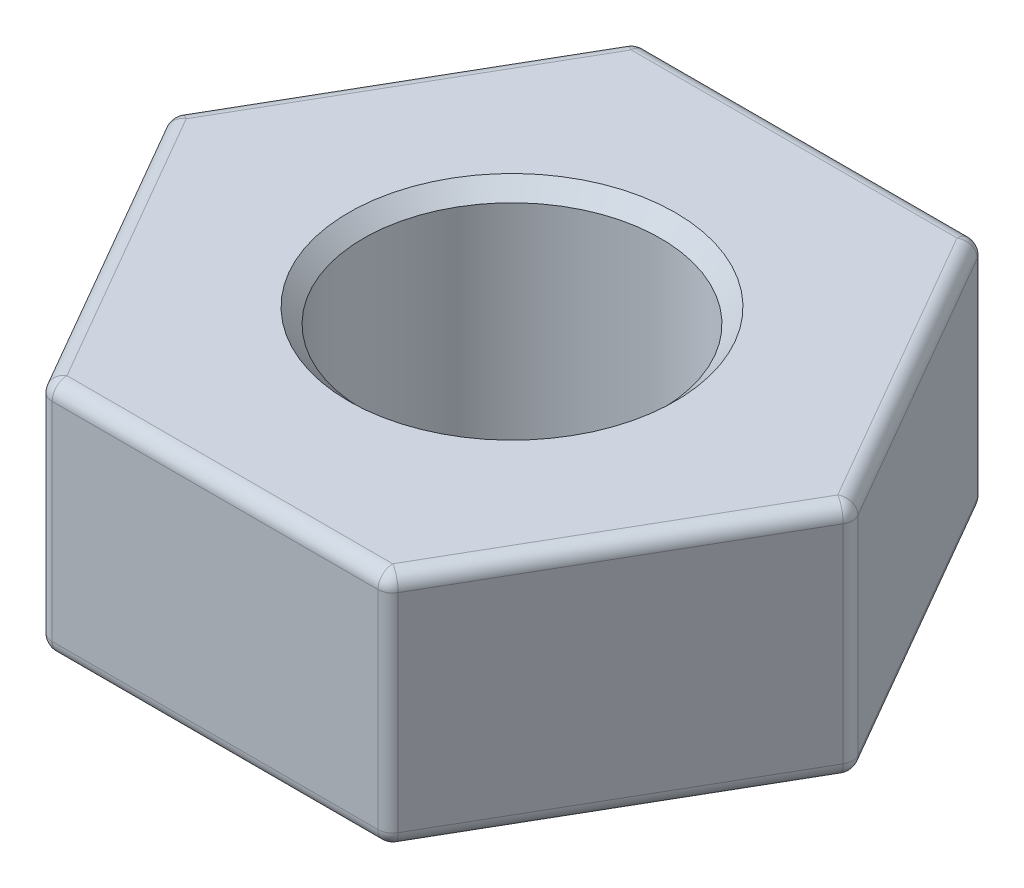
SolidWorks part; units mm, degrees
material "AISI 304"
ref_plane "前视基准面" through (0, 0, 0) normal (0, 0, 1) x (1, 0, 0)
ref_plane "上视基准面" through (0, 0, 0) normal (0, 1, 0) x (1, 0, 0)
ref_plane "右视基准面" through (0, 0, 0) normal (1, 0, 0) x (0, 0, -1)
sketch "草图2" plane through (0, 0, 0) normal (0, 1, 0) x (1, 0, 0)
  line L1 (2.3094, 0) -> (1.1547, 2)
  line L2 (1.1547, 2) -> (-1.1547, 2)
  line L3 (-1.1547, 2) -> (-2.3094, 0)
  line L4 (-2.3094, 0) -> (-1.1547, -2)
  line L5 (-1.1547, -2) -> (1.1547, -2)
  line L6 (1.1547, -2) -> (2.3094, 0)
  circle A0 centre (0, 0) radius 2 construction
  circle A1 centre (0, 0) radius 1
  dimension "D2" = 2
  dimension "D1" = 4
extrude "凸台-拉伸1" add sketch "草图2" along normal blind 1.6
fillet "圆角1" radius 0.1 18 edges at (-1.7321, 0, 1) (-1.7321, 0, -1) (0, 0, -2) (1.7321, 0, -1) (1.7321, 0, 1) (0, 0, 2) (1.1547, 0.8, 2) (-1.1547, 0.8, 2) (-2.3094, 0.8, 0) (-1.1547, 0.8, -2) (1.1547, 0.8, -2) (2.3094, 0.8, 0) (-1.7321, 1.6, 1) (-1.7321, 1.6, -1) (0, 1.6, -2) (1.7321, 1.6, -1) (1.7321, 1.6, 1) (0, 1.6, 2)
chamfer "倒角1" distance 0.1 angle 45 2 edges at (0, 0, 1) (0, 1.6, 1)
